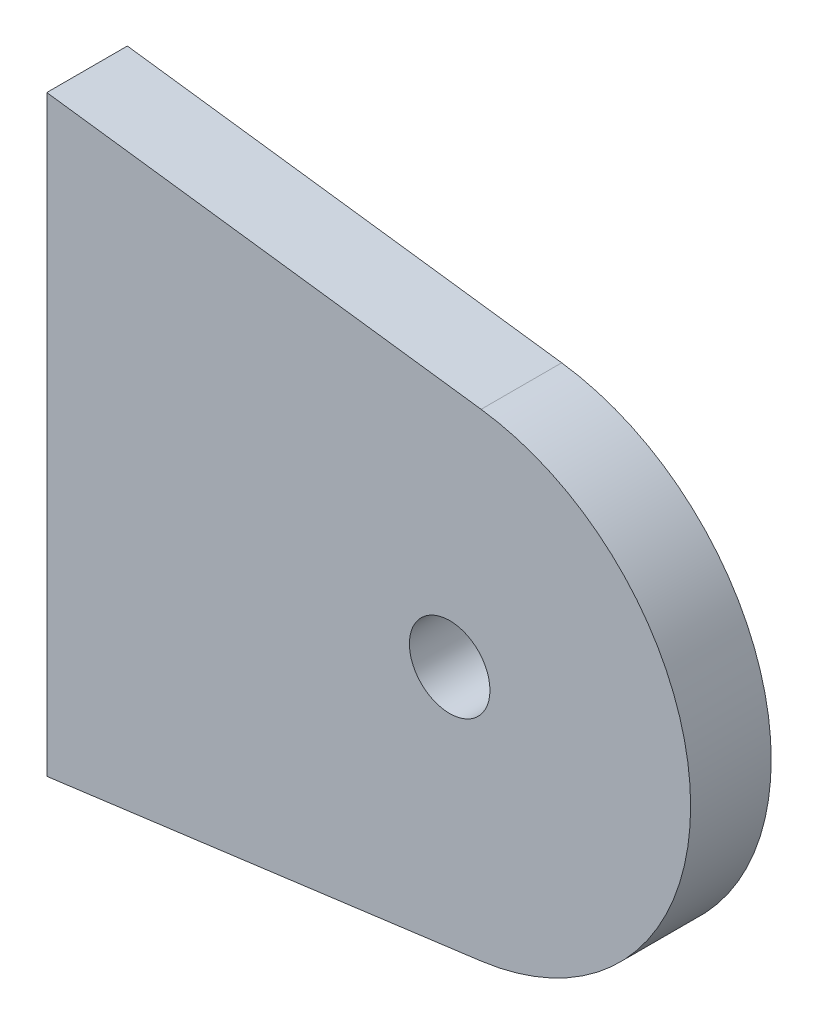
SolidWorks part; units mm, degrees
material "AISI 4130 Steel, annealed at 865C"
ref_plane "X-Y Datum" through (0, 0, 0) normal (0, 0, 1) x (1, 0, 0)
ref_plane "X-Z Datum" through (0, 0, 0) normal (0, 1, 0) x (1, 0, 0)
ref_plane "Y-Z Datum" through (0, 0, 0) normal (1, 0, 0) x (0, 0, -1)
sketch "Sketch1" plane through (-1053.7408, 0, 0) normal (0, 0, 1) x (1, 0, 0)
  line L0 (1054.9803, -9.4147) -> (1037.8658, -11.6679)
  line L1 (1054.9803, 9.4147) -> (1037.8658, 11.6679)
  line L2 (1037.8658, -11.6679) -> (1037.8658, 11.6679)
  circle A0 centre (1053.7408, 0) radius 1.5875
  circle A1 centre (1053.7408, 0) radius 9.4959
  circle A4 centre (1053.7408, 0) radius 11.43 construction
  dimension "D3" = 18.9919
  dimension "D4" = 3.175
  dimension "D5" = 22.86
  dimension "D1" = 15
  dimension "D2" = 15.875
extrude "Boss-Extrude1" add sketch "Sketch1" along normal blind 3.175
